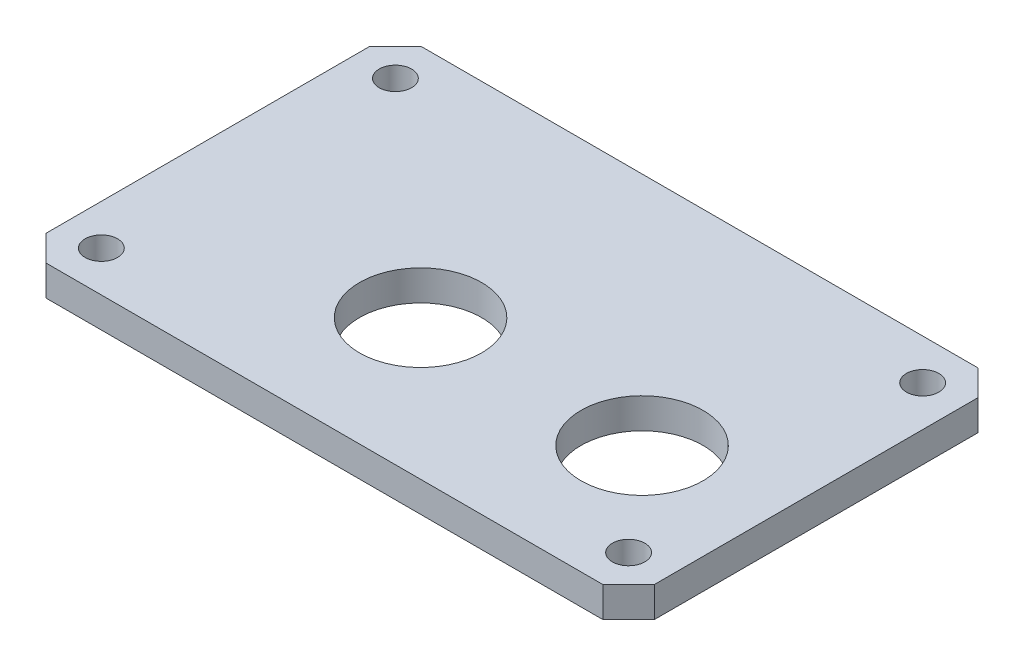
SolidWorks part; units mm, degrees
ref_plane "Front Plane" through (0, 0, 0) normal (0, 0, 1) x (1, 0, 0)
ref_plane "Top Plane" through (0, 0, 0) normal (0, 1, 0) x (1, 0, 0)
ref_plane "Right Plane" through (0, 0, 0) normal (1, 0, 0) x (0, 0, -1)
sketch "Sketch1" plane through (0, 0, 0) normal (0, 1, 0) x (1, 0, 0)
  line L1 (-30, -18.5) -> (30, -18.5)
  line L2 (-30, -18.5) -> (-30, 18.5)
  line L3 (-30, 18.5) -> (30, 18.5)
  line L4 (30, -18.5) -> (30, 18.5)
  line L5 (-30, -18.5) -> (30, 18.5) construction
  line L6 (-30, 18.5) -> (30, -18.5) construction
  point P0 (0, 0)
  dimension "D1" = 37
  dimension "D2" = 60
extrude "Boss-Extrude1" add sketch "Sketch1" along normal blind 2.9972
sketch "Sketch2" plane through (0, 2.9972, 0) normal (0, 1, 0) x (1, 0, 0)
  line L0 (30, 18.5) -> (-30, 18.5) construction
  line L1 (-26, -14.5) -> (26, -14.5) construction
  line L2 (-26, -14.5) -> (-26, 14.5) construction
  line L3 (-26, 14.5) -> (26, 14.5) construction
  line L4 (26, -14.5) -> (26, 14.5) construction
  line L5 (-26, -14.5) -> (26, 14.5) construction
  line L6 (-26, 14.5) -> (26, -14.5) construction
  line L7 (30, -18.5) -> (30, 18.5) construction
  circle A0 centre (-26, 14.5) radius 1.6
  circle A1 centre (-26, -14.5) radius 1.6
  circle A2 centre (26, -14.5) radius 1.6
  circle A3 centre (26, 14.5) radius 1.6
  point P12 (0, 0)
  dimension "D1" = 3.2
  dimension "D2" = 4
  dimension "D3" = 4
extrude "Cut-Extrude1" cut sketch "Sketch2" against normal through all
sketch "Sketch3" plane through (0, 2.9972, 0) normal (0, 1, 0) x (1, 0, 0)
  line L0 (-4.318, -4.699) -> (17.526, -4.699) construction
  line L1 (0, 0) -> (17.526, 0) construction
  line L2 (17.526, 0) -> (17.526, -4.699) construction
  line L5 (-4.318, 0) -> (-4.318, -4.699) construction
  line L6 (-4.318, 0) -> (0, 0) construction
  circle A0 centre (-4.318, -4.699) radius 6.0198
  circle A1 centre (17.526, -4.699) radius 6.0198
  dimension "D1" = 12.0396
  dimension "D2" = 17.526
  dimension "D3" = 4.699
  dimension "D4" = 4.318
extrude "Cut-Extrude2" cut sketch "Sketch3" against normal through all
chamfer "Chamfer1" distance 2.54 angle 45 4 edges at (30, 1.4986, -18.5) (30, 1.4986, 18.5) (-30, 1.4986, 18.5) (-30, 1.4986, -18.5)
